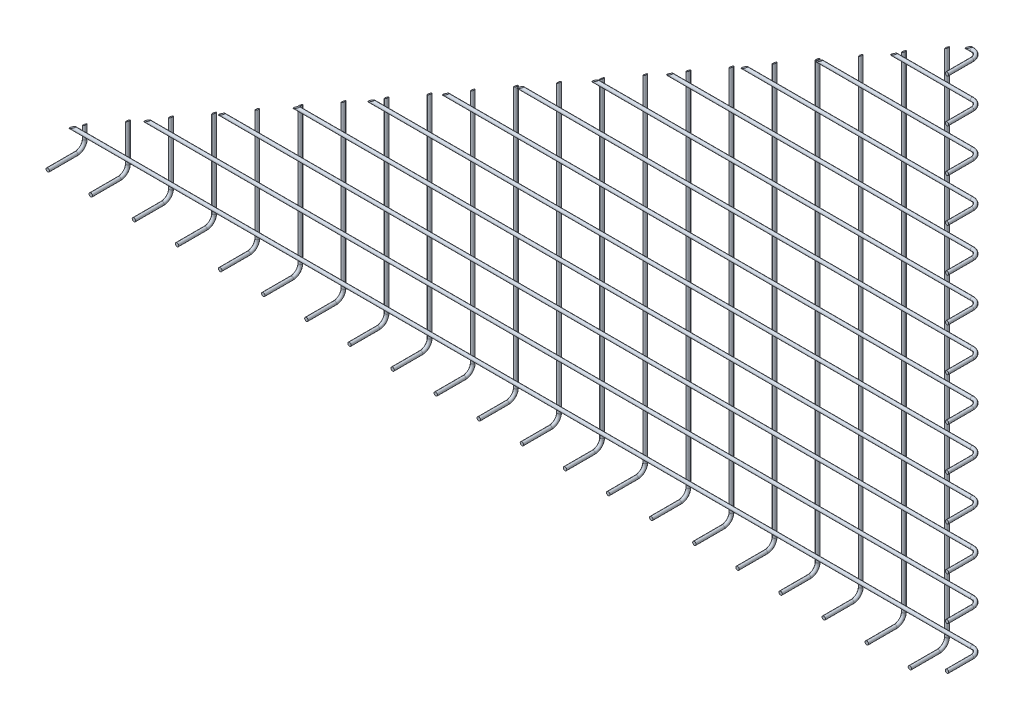
SolidWorks part; units mm, degrees
material "AISI 1020"
ref_plane "Спереди" through (0, 0, 0) normal (0, 0, 1) x (1, 0, 0)
ref_plane "Сверху" through (0, 0, 0) normal (0, 1, 0) x (1, 0, 0)
ref_plane "Справа" through (0, 0, 0) normal (1, 0, 0) x (0, 0, -1)
sketch "Эскиз1" plane through (0, 0, 47) normal (0, 0, 1) x (1, 0, 0)
  line L1 (-545, 0) -> (545, 0) construction
  circle A0 centre (0, 2) radius 2
  dimension "D1" = 4
sketch "Эскиз2" plane through (0, 0, 0) normal (1, 0, 0) x (0, 0, -1)
  line L0 (-47, 2) -> (-14, 2)
  line L1 (-4, 12) -> (-4, 851.0566)
  line L2 (-47, 4) -> (-47, 0) construction
  line L4 (-47, 4) -> (-47, 0) construction
  line L5 (-0.75, 836.0566) -> (-22, 836.0566) construction
  line L6 (-2, 851.0566) -> (-6, 851.0566) construction
  line L7 (-2, -325) -> (-2, 2528.5605) construction
  arc A0 (-14, 2) -> (-4, 12) centre (-14, 12) ccw
  point P5 (-4, 851.0566)
  point P6 (-47, 2)
  dimension "D2" = 10
  dimension "D1" = 15
sweep "По траектории1" add profiles "Эскиз1" path "Эскиз2"
pattern_linear "Линейный массив1" count 11 spacing 50 along (1, 0, 0) of bodies 103
mirror "Зеркальное отражение1" about plane through (0, 0, 0) normal (1, 0, 0) of bodies 113 112 111 110 109 108 107 106 105 104
ref_plane "Плоскость1" through (0, 20, 0) normal (0, 1, 0) x (1, 0, 0)
sketch "Эскиз3" plane through (0, 20, 0) normal (0, 1, 0) x (1, 0, 0)
  line L0 (-543, -47) -> (-543, -18)
  line L1 (-533, -8) -> (533, -8)
  line L2 (543, -18) -> (543, -47)
  line L3 (545, -44) -> (545, 0) construction
  line L4 (-545, 0) -> (-545, -44) construction
  line L5 (-545, -47) -> (545, -47) construction
  circle A0 centre (500, -4) radius 2 construction
  arc A1 (533, -8) -> (543, -18) centre (533, -18) cw
  arc A2 (-543, -18) -> (-533, -8) centre (-533, -18) cw
  dimension "D2" = 4
  dimension "D4" = 10
  dimension "D1" = 2
  dimension "D3" = 2
sketch "Эскиз4" plane through (0, 0, 47) normal (0, 0, 1) x (1, 0, 0)
  circle A0 centre (543, 20) radius 2
  dimension "D1" = 4
sweep "По траектории2" add profiles "Эскиз4" path "Эскиз3"
pattern_linear "Линейный массив2" count 17 spacing 50 along (0, 1, 0) of bodies 124
sketch "Эскиз5" plane through (0, 0, 0) normal (0, 0, 1) x (1, 0, 0)
  line L0 (545, 629.3118) -> (545, 0)
  line L1 (545, 0) -> (-545, 0)
  line L2 (-545, 0) -> (545, 629.3118)
  line L3 (545, -2197.1132) -> (545, 629.3118) construction
  line L4 (-545, 0) -> (545, 0) construction
  line L5 (1102.5, 951.1846) -> (-676.6025, -75.9808) construction
extrude "Вырез-Вытянуть1" cut sketch "Эскиз5" against normal through all both and the other way through all flip side to cut
